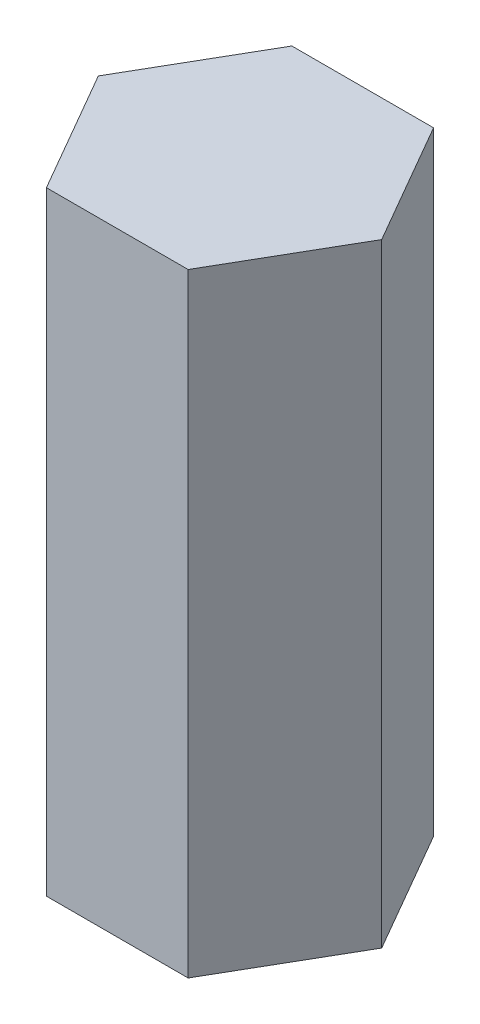
SolidWorks part; units mm, degrees
ref_plane "Front Plane" through (0, 0, 0) normal (0, 0, 1) x (1, 0, 0)
ref_plane "Top Plane" through (0, 0, 0) normal (0, 1, 0) x (1, 0, 0)
ref_plane "Right Plane" through (0, 0, 0) normal (1, 0, 0) x (0, 0, -1)
sketch "Sketch1" plane through (0, 0, 0) normal (0, 1, 0) x (1, 0, 0)
  line L1 (1.7321, 3) -> (-1.7321, 3)
  line L2 (-1.7321, 3) -> (-3.4641, 0)
  line L3 (-3.4641, 0) -> (-1.7321, -3)
  line L4 (-1.7321, -3) -> (1.7321, -3)
  line L5 (1.7321, -3) -> (3.4641, 0)
  line L6 (3.4641, 0) -> (1.7321, 3)
  circle A0 centre (0, 0) radius 3 construction
  point P1 (0, 3)
  dimension "D1" = 6
extrude "Boss-Extrude1" add sketch "Sketch1" along normal blind 15
